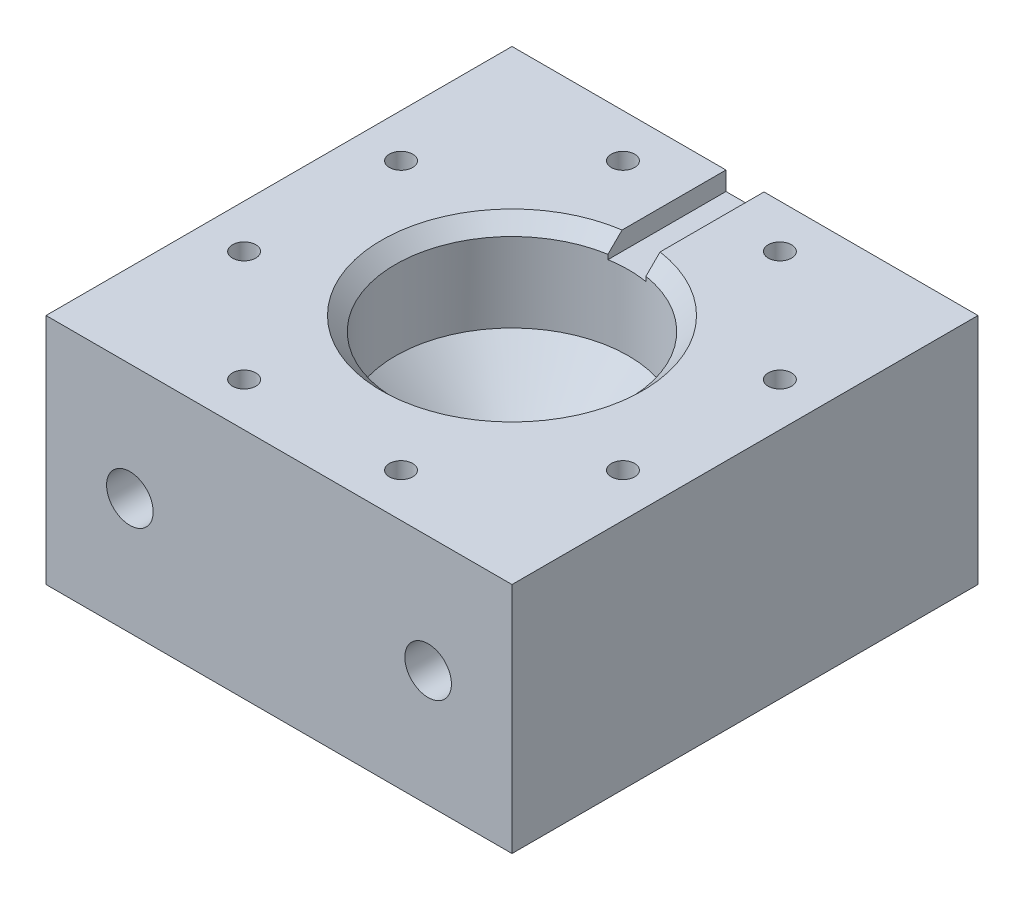
SolidWorks part; units mm, degrees
material "Alliage 1060"
ref_plane "Front" through (0, 0, 0) normal (0, 0, 1) x (1, 0, 0)
ref_plane "Top" through (0, 0, 0) normal (0, 1, 0) x (1, 0, 0)
ref_plane "Right" through (0, 0, 0) normal (1, 0, 0) x (0, 0, -1)
other "filet"
sketch "Esquisse1" plane through (0, 0, 0) normal (0, 1, 0) x (1, 0, 0)
  line L1 (-25, 25) -> (25, 25)
  line L2 (-25, 25) -> (-25, -25)
  line L3 (-25, -25) -> (25, -25)
  line L4 (25, 25) -> (25, -25)
  line L5 (-25, 25) -> (25, -25) construction
  line L6 (-25, -25) -> (25, 25) construction
  point P0 (0, 0)
  dimension "D1" = 50
extrude "Boss.-Extru.1" add sketch "Esquisse1" along normal blind 25
sketch "Esquisse2" plane through (0, 0, 0) normal (0, 0, 1) x (1, 0, 0)
  line L0 (0, 0) -> (0, 25) construction
  line L1 (-25, 25) -> (25, 25) construction
  line L2 (0, 0) -> (4.5, 0)
  line L3 (-25, 0) -> (25, 0) construction
  line L4 (4.5, 0) -> (4.5, 7)
  line L5 (4.5, 7) -> (12.5, 15)
  line L6 (12.5, 15) -> (12.5, 25)
  line L7 (12.5, 25) -> (0, 25)
  line L9 (0, 25) -> (0, 0)
  dimension "D1" = 9
  dimension "D2" = 7
  dimension "D3" = 10
  dimension "D4" = 135
revolve "Enlèvement de matière-Révolution1" cut sketch "Esquisse2" angle 360 about L0
hole_wizard "Trou pour taraudage pour trou taraudé M31" positions "Esquisse8" profile "Esquisse9" hole size "M3" standard "ISO"
sketch "Esquisse8" plane through (0, 25, 0) normal (0, 1, 0) x (1, 0, 0)
  line L0 (0, 0) -> (0, 25) construction
  line L1 (25, 25) -> (-25, 25) construction
  line L3 (-8.419, 20.3253) -> (0, 0) construction
  line L5 (8.419, -20.3253) -> (0, 0) construction
  point P0 (-8.419, 20.3253)
  point P18 (8.419, 20.3253)
  point P19 (20.3253, 8.419)
  point P20 (20.3253, -8.419)
  point P21 (8.419, -20.3253)
  point P22 (-8.419, -20.3253)
  point P23 (-20.3253, -8.419)
  point P24 (-20.3253, 8.419)
  dimension "D1" = 22.5
  dimension "D2" = 22
  dimension "D3" = 8
sketch "Esquisse9" plane through (-8.419, 25, -20.3253) normal (1, 0, 0) x (0, 0, 1)
  line L0 (0, 0) -> (0, 10.7511)
  line L1 (0, 10.7511) -> (1.25, 10)
  line L2 (1.25, 10) -> (1.25, 0)
  line L5 (1.25, 0) -> (0, 0)
  line L10 (0, 10.7511) -> (-1.25, 10) construction
  line L11 (0, -6.35) -> (0, 107.95) construction
  dimension "Diamètre du perçage" = 2.5
  dimension "Profondeur du perçage" = 10
  dimension "Angle de pointe" = 118
hole_wizard "Trou pour taraudage pour trou taraudé M61" positions "Esquisse10" profile "Esquisse11" hole size "M6" standard "ISO"
sketch "Esquisse10" plane through (0, 0, 25) normal (0, 0, 1) x (1, 0, 0)
  line L0 (16, 12.5) -> (-16, 12.5) construction
  line L2 (-25, 25) -> (25, 25) construction
  line L3 (0, 25) -> (0, 0) construction
  point P0 (-16, 12.5)
  point P2 (16, 12.5)
  point P15 (0, 12.5)
  point P16 (0, 12.5)
  dimension "D1" = 32
sketch "Esquisse11" plane through (-16, 12.5, 25) normal (1, 0, 0) x (0, -1, 0)
  line L0 (0, 0) -> (0, 11.5022)
  line L1 (0, 11.5022) -> (2.5, 10)
  line L2 (2.5, 10) -> (2.5, 0)
  line L5 (2.5, 0) -> (0, 0)
  line L10 (0, 11.5022) -> (-2.5, 10) construction
  line L11 (0, -6.35) -> (0, 107.95) construction
  dimension "Diamètre du perçage" = 5
  dimension "Profondeur du perçage" = 10
  dimension "Angle de pointe" = 118
sketch "Esquisse12" plane through (0, 25, 0) normal (0, 1, 0) x (1, 0, 0)
  line L0 (25, 25) -> (-25, 25) construction
  line L1 (-2.0394, 25) -> (2.0394, 25)
  line L2 (-2.0394, 25) -> (-2.0394, 11)
  line L3 (-2.0394, 11) -> (2.0394, 11)
  line L4 (2.0394, 25) -> (2.0394, 11)
  line L5 (-2.0394, 25) -> (2.0394, 11) construction
  line L6 (-2.0394, 11) -> (2.0394, 25) construction
  point P0 (0, 18)
  dimension "D1" = 14
extrude "Enlèv. mat.-Extru.1" cut sketch "Esquisse12" against normal blind 2
chamfer "Chanfrein1" distance 1.5 angle 45 1 edges at (0, 25, 12.5)
